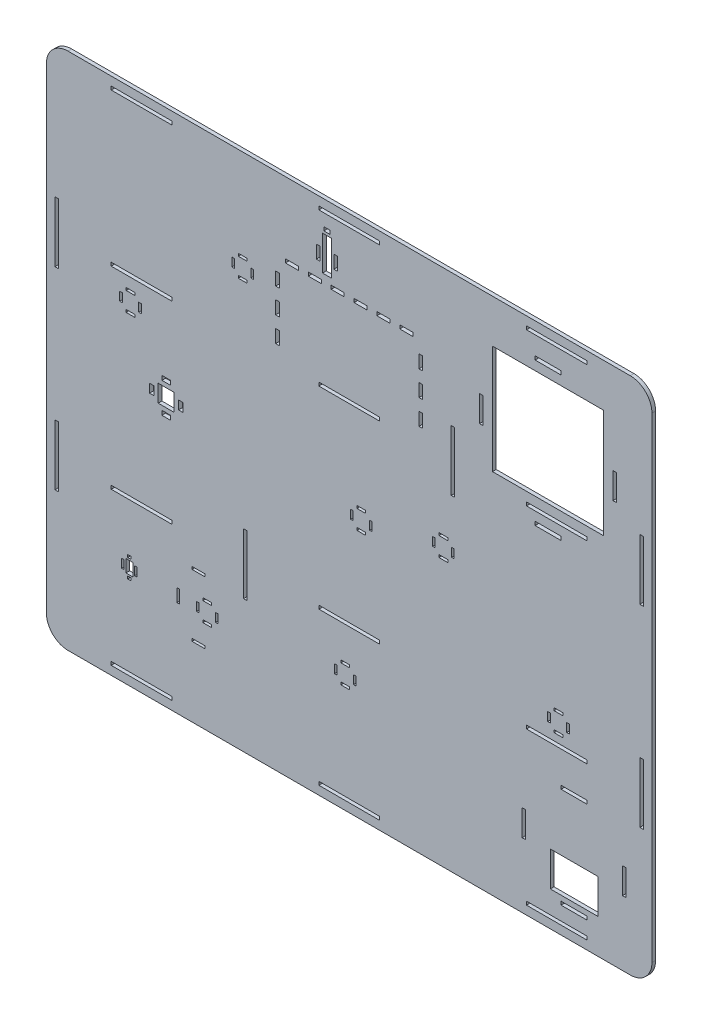
SolidWorks part; units mm, degrees
ref_plane "Front Plane" through (0, 0, 0) normal (0, 0, 1) x (1, 0, 0)
ref_plane "Top Plane" through (0, 0, 0) normal (0, 1, 0) x (1, 0, 0)
ref_plane "Right Plane" through (0, 0, 0) normal (1, 0, 0) x (0, 0, -1)
sketch "Sketch1" plane through (0, 0, 0) normal (0, 0, 1) x (1, 0, 0)
  line L0 (82.85, 113.55) -> (82.85, 215.7) construction
  line L1 (-325, -300) -> (325, -300)
  line L2 (-350, -275) -> (-350, 275)
  line L3 (-325, 300) -> (325, 300)
  line L4 (350, -275) -> (350, 275)
  line L5 (-350, -300) -> (350, 300) construction
  line L6 (-350, 300) -> (350, -300) construction
  line L7 (82.85, 215.7) -> (-82.85, 215.7) construction
  line L8 (-82.85, 215.7) -> (-82.85, 113.55) construction
  line L9 (-35.85, 215.7) -> (-35.85, 270) construction
  line L10 (-35.85, 270) -> (-15.55, 270) construction
  line L11 (-15.55, 270) -> (-15.55, 215.7) construction
  line L12 (-80.75, 142.31) -> (-84.95, 127.21) construction
  line L13 (80.75, 199.87) -> (84.95, 199.87)
  line L14 (80.75, 199.87) -> (80.75, 184.77)
  line L15 (0, 300) -> (0, -300) construction
  line L16 (-350, 0) -> (350, 0) construction
  line L17 (-275, -286) -> (-275, -290)
  line L18 (340, -76.6666) -> (336, -76.6666)
  line L19 (340, -76.6666) -> (340, -146.6666)
  line L20 (340, -146.6666) -> (336, -146.6666)
  line L21 (336, -76.6666) -> (336, -146.6666)
  line L22 (336, 146.6667) -> (340, 146.6667)
  line L23 (336, 146.6667) -> (336, 76.6667)
  line L24 (336, 76.6667) -> (340, 76.6667)
  line L25 (340, 146.6667) -> (340, 76.6667)
  line L30 (-35, -286) -> (35, -286)
  line L31 (-35, -286) -> (-35, -290)
  line L32 (-35, -290) -> (35, -290)
  line L33 (35, -286) -> (35, -290)
  line L34 (205, -286) -> (275, -286)
  line L35 (205, -286) -> (205, -290)
  line L36 (205, -290) -> (275, -290)
  line L37 (275, -286) -> (275, -290)
  line L38 (-205, -290) -> (-275, -290)
  line L39 (-205, -286) -> (-205, -290)
  line L40 (-205, -286) -> (-275, -286)
  line L45 (-340, 146.6667) -> (-340, 76.6667)
  line L46 (-336, 76.6667) -> (-340, 76.6667)
  line L47 (-336, 146.6667) -> (-336, 76.6667)
  line L48 (-336, 146.6667) -> (-340, 146.6667)
  line L49 (-336, -76.6666) -> (-336, -146.6666)
  line L50 (-340, -146.6666) -> (-336, -146.6666)
  line L51 (-340, -76.6666) -> (-340, -146.6666)
  line L52 (-340, -76.6666) -> (-336, -76.6666)
  line L61 (80.75, 184.77) -> (84.95, 184.77)
  line L62 (84.95, 199.87) -> (84.95, 184.77)
  line L63 (80.75, 199.87) -> (84.95, 184.77) construction
  line L64 (-340, 290) -> (340, 290) construction
  line L65 (340, -290) -> (340, 290) construction
  line L66 (-340, -290) -> (340, -290) construction
  line L67 (-340, -290) -> (-340, 290) construction
  line L72 (122, 146.6667) -> (118, 146.6667)
  line L73 (122, 146.6667) -> (122, 76.6667)
  line L74 (122, 76.6667) -> (118, 76.6667)
  line L75 (118, 146.6667) -> (118, 76.6667)
  line L80 (-330, 280) -> (330, 280) construction
  line L81 (330, -280) -> (330, 280) construction
  line L82 (-330, -280) -> (330, -280) construction
  line L83 (-330, -280) -> (-330, 280) construction
  line L84 (-118, -146.6667) -> (-118, -76.6667)
  line L85 (-118, -76.6667) -> (-122, -76.6667)
  line L86 (-122, -146.6667) -> (-122, -76.6667)
  line L87 (-118, -146.6667) -> (-122, -146.6667)
  line L92 (-35, 113.6667) -> (35, 113.6667)
  line L93 (-35, 113.6667) -> (-35, 109.6667)
  line L94 (-35, 109.6667) -> (35, 109.6667)
  line L95 (35, 113.6667) -> (35, 109.6667)
  line L96 (-275, 113.6667) -> (-205, 113.6667)
  line L97 (-275, 113.6667) -> (-275, 109.6667)
  line L98 (-275, 109.6667) -> (-205, 109.6667)
  line L99 (-205, 113.6667) -> (-205, 109.6667)
  line L100 (205, 113.6667) -> (275, 113.6667)
  line L101 (205, 113.6667) -> (205, 109.6667)
  line L102 (205, 109.6667) -> (275, 109.6667)
  line L103 (275, 113.6667) -> (275, 109.6667)
  line L104 (-275, -113.6667) -> (-275, -109.6667)
  line L105 (-275, -109.6667) -> (-205, -109.6667)
  line L106 (-205, -113.6667) -> (-205, -109.6667)
  line L107 (-275, -113.6667) -> (-205, -113.6667)
  line L108 (-35, -113.6667) -> (-35, -109.6667)
  line L109 (-35, -109.6667) -> (35, -109.6667)
  line L110 (35, -113.6667) -> (35, -109.6667)
  line L111 (-35, -113.6667) -> (35, -113.6667)
  line L112 (205, -113.6667) -> (205, -109.6667)
  line L113 (205, -109.6667) -> (275, -109.6667)
  line L114 (275, -113.6667) -> (275, -109.6667)
  line L115 (205, -113.6667) -> (275, -113.6667)
  line L116 (-205, 286) -> (-275, 286)
  line L117 (-205, 286) -> (-205, 290)
  line L118 (-205, 290) -> (-275, 290)
  line L119 (-275, 286) -> (-275, 290)
  line L120 (-35, 290) -> (35, 290)
  line L121 (35, 286) -> (35, 290)
  line L122 (-35, 286) -> (35, 286)
  line L123 (-35, 286) -> (-35, 290)
  line L124 (205, 290) -> (275, 290)
  line L125 (275, 286) -> (275, 290)
  line L126 (205, 286) -> (275, 286)
  line L127 (205, 286) -> (205, 290)
  line L128 (-338, -288) -> (-338, 288) construction
  line L129 (-338, 288) -> (338, 288) construction
  line L130 (338, -288) -> (338, 288) construction
  line L131 (-338, -288) -> (338, -288) construction
  line L132 (80.75, 184.77) -> (84.95, 199.87) construction
  line L133 (80.75, 155.99) -> (84.95, 155.99)
  line L134 (80.75, 155.99) -> (80.75, 171.09)
  line L135 (80.75, 171.09) -> (84.95, 171.09)
  line L136 (84.95, 155.99) -> (84.95, 171.09)
  line L137 (80.75, 155.99) -> (84.95, 171.09) construction
  line L138 (80.75, 171.09) -> (84.95, 155.99) construction
  line L139 (80.75, 127.21) -> (84.95, 127.21)
  line L140 (80.75, 127.21) -> (80.75, 142.31)
  line L141 (80.75, 142.31) -> (84.95, 142.31)
  line L142 (84.95, 127.21) -> (84.95, 142.31)
  line L143 (80.75, 127.21) -> (84.95, 142.31) construction
  line L144 (80.75, 142.31) -> (84.95, 127.21) construction
  line L145 (-80.75, 127.21) -> (-84.95, 142.31) construction
  line L146 (-80.75, 171.09) -> (-84.95, 155.99) construction
  line L147 (-80.75, 155.99) -> (-84.95, 171.09) construction
  line L148 (-80.75, 184.77) -> (-84.95, 199.87) construction
  line L149 (-80.75, 199.87) -> (-84.95, 184.77) construction
  line L150 (-84.95, 127.21) -> (-84.95, 142.31)
  line L151 (-80.75, 142.31) -> (-84.95, 142.31)
  line L152 (-80.75, 127.21) -> (-80.75, 142.31)
  line L153 (-80.75, 127.21) -> (-84.95, 127.21)
  line L154 (-84.95, 155.99) -> (-84.95, 171.09)
  line L155 (-80.75, 171.09) -> (-84.95, 171.09)
  line L156 (-80.75, 155.99) -> (-80.75, 171.09)
  line L157 (-80.75, 155.99) -> (-84.95, 155.99)
  line L158 (-84.95, 199.87) -> (-84.95, 184.77)
  line L159 (-80.75, 184.77) -> (-84.95, 184.77)
  line L160 (-80.75, 199.87) -> (-80.75, 184.77)
  line L161 (-80.75, 199.87) -> (-84.95, 199.87)
  line L162 (320, -270) -> (320, -150) construction
  line L163 (-73.65, 213.6) -> (-58.55, 213.6)
  line L164 (-73.65, 213.6) -> (-73.65, 217.8)
  line L165 (-73.65, 217.8) -> (-58.55, 217.8)
  line L166 (-58.55, 213.6) -> (-58.55, 217.8)
  line L167 (-73.65, 213.6) -> (-58.55, 217.8) construction
  line L168 (-73.65, 217.8) -> (-58.55, 213.6) construction
  line L169 (-47.21, 213.6) -> (-32.11, 213.6)
  line L170 (-47.21, 213.6) -> (-47.21, 217.8)
  line L171 (-47.21, 217.8) -> (-32.11, 217.8)
  line L172 (-32.11, 213.6) -> (-32.11, 217.8)
  line L173 (-47.21, 213.6) -> (-32.11, 217.8) construction
  line L174 (-47.21, 217.8) -> (-32.11, 213.6) construction
  line L175 (-20.77, 213.6) -> (-5.67, 213.6)
  line L176 (-20.77, 213.6) -> (-20.77, 217.8)
  line L177 (-20.77, 217.8) -> (-5.67, 217.8)
  line L178 (-5.67, 213.6) -> (-5.67, 217.8)
  line L179 (-20.77, 213.6) -> (-5.67, 217.8) construction
  line L180 (-20.77, 217.8) -> (-5.67, 213.6) construction
  line L181 (5.67, 213.6) -> (20.77, 213.6)
  line L182 (5.67, 213.6) -> (5.67, 217.8)
  line L183 (5.67, 217.8) -> (20.77, 217.8)
  line L184 (20.77, 213.6) -> (20.77, 217.8)
  line L185 (5.67, 213.6) -> (20.77, 217.8) construction
  line L186 (5.67, 217.8) -> (20.77, 213.6) construction
  line L187 (32.11, 213.6) -> (47.21, 213.6)
  line L188 (32.11, 213.6) -> (32.11, 217.8)
  line L189 (32.11, 217.8) -> (47.21, 217.8)
  line L190 (47.21, 213.6) -> (47.21, 217.8)
  line L191 (32.11, 213.6) -> (47.21, 217.8) construction
  line L192 (32.11, 217.8) -> (47.21, 213.6) construction
  line L193 (58.55, 213.6) -> (73.65, 213.6)
  line L194 (58.55, 213.6) -> (58.55, 217.8)
  line L195 (58.55, 217.8) -> (73.65, 217.8)
  line L196 (73.65, 213.6) -> (73.65, 217.8)
  line L197 (58.55, 213.6) -> (73.65, 217.8) construction
  line L198 (58.55, 217.8) -> (73.65, 213.6) construction
  line L199 (-17.65, 250.4) -> (-13.45, 250.4)
  line L200 (-17.65, 250.4) -> (-17.65, 235.3)
  line L201 (-17.65, 235.3) -> (-13.45, 235.3)
  line L202 (-13.45, 250.4) -> (-13.45, 235.3)
  line L203 (-17.65, 250.4) -> (-13.45, 235.3) construction
  line L204 (-17.65, 235.3) -> (-13.45, 250.4) construction
  line L205 (-37.95, 250.4) -> (-33.75, 250.4)
  line L206 (-37.95, 250.4) -> (-37.95, 235.3)
  line L207 (-37.95, 235.3) -> (-33.75, 235.3)
  line L208 (-33.75, 250.4) -> (-33.75, 235.3)
  line L209 (-37.95, 250.4) -> (-33.75, 235.3) construction
  line L210 (-37.95, 235.3) -> (-33.75, 250.4) construction
  line L211 (-29.25, 267.9) -> (-22.15, 267.9)
  line L212 (-29.25, 267.9) -> (-29.25, 272.1)
  line L213 (-29.25, 272.1) -> (-22.15, 272.1)
  line L214 (-22.15, 267.9) -> (-22.15, 272.1)
  line L215 (-29.25, 267.9) -> (-22.15, 272.1) construction
  line L216 (-29.25, 272.1) -> (-22.15, 267.9) construction
  line L217 (-30.75, 264.9) -> (-20.65, 264.9)
  line L218 (-30.75, 264.9) -> (-30.75, 224.9)
  line L219 (-30.75, 224.9) -> (-20.65, 224.9)
  line L220 (-20.65, 264.9) -> (-20.65, 224.9)
  line L221 (320, -150) -> (200, -150) construction
  line L222 (200, -150) -> (200, -270) construction
  line L223 (200, -270) -> (320, -270) construction
  line L224 (229.5, -101.3683) -> (254.5, -101.3683) construction
  line L225 (275, -270) -> (245, -270)
  line L226 (275, -270) -> (275, -266)
  line L227 (275, -266) -> (245, -266)
  line L228 (245, -270) -> (245, -266)
  line L229 (200, -225) -> (204, -225)
  line L230 (200, -225) -> (200, -195)
  line L231 (200, -195) -> (204, -195)
  line L232 (204, -225) -> (204, -195)
  line L233 (245, -150) -> (275, -150)
  line L234 (245, -150) -> (245, -154)
  line L235 (245, -154) -> (275, -154)
  line L236 (275, -150) -> (275, -154)
  line L237 (320, -195) -> (316, -195)
  line L238 (320, -195) -> (320, -225)
  line L239 (320, -225) -> (316, -225)
  line L240 (316, -195) -> (316, -225)
  line L241 (232.5, -260) -> (287.5, -260)
  line L242 (232.5, -260) -> (232.5, -220)
  line L243 (232.5, -220) -> (287.5, -220)
  line L244 (287.5, -260) -> (287.5, -220)
  line L245 (-263, -193.95) -> (-245, -193.95) construction
  line L246 (-263, -193.95) -> (-263, -169.45) construction
  line L247 (-263, -169.45) -> (-245, -169.45) construction
  line L248 (-245, -193.95) -> (-245, -169.45) construction
  line L249 (-245, -176.7) -> (-248, -176.7)
  line L250 (-245, -176.7) -> (-245, -186.7)
  line L251 (-245, -186.7) -> (-248, -186.7)
  line L252 (-248, -176.7) -> (-248, -186.7)
  line L253 (-256, -193.95) -> (-252, -193.95)
  line L254 (-256, -193.95) -> (-256, -190.95)
  line L255 (-256, -190.95) -> (-252, -190.95)
  line L256 (-252, -193.95) -> (-252, -190.95)
  line L257 (-263, -186.7) -> (-260, -186.7)
  line L258 (-263, -186.7) -> (-263, -176.7)
  line L259 (-263, -176.7) -> (-260, -176.7)
  line L260 (-260, -186.7) -> (-260, -176.7)
  line L261 (-256, -169.45) -> (-252, -169.45)
  line L262 (-256, -169.45) -> (-256, -172.45)
  line L263 (-256, -172.45) -> (-252, -172.45)
  line L264 (-252, -169.45) -> (-252, -172.45)
  line L265 (-230.7, -10.34) -> (-192.2, -10.34) construction
  line L266 (-230.7, -10.34) -> (-230.7, 29.66) construction
  line L267 (-230.7, 29.66) -> (-192.2, 29.66) construction
  line L268 (-192.2, -10.34) -> (-192.2, 29.66) construction
  line L269 (-192.2, 14.66) -> (-197.2, 14.66)
  line L270 (-192.2, 14.66) -> (-192.2, 4.66)
  line L271 (-192.2, 4.66) -> (-197.2, 4.66)
  line L272 (-197.2, 14.66) -> (-197.2, 4.66)
  line L273 (-230.7, 14.66) -> (-225.7, 14.66)
  line L274 (-230.7, 14.66) -> (-230.7, 4.66)
  line L275 (-230.7, 4.66) -> (-225.7, 4.66)
  line L276 (-225.7, 14.66) -> (-225.7, 4.66)
  line L277 (-206.45, -10.34) -> (-216.45, -10.34)
  line L278 (-206.45, -10.34) -> (-206.45, -5.34)
  line L279 (-206.45, -5.34) -> (-216.45, -5.34)
  line L280 (-216.45, -10.34) -> (-216.45, -5.34)
  line L281 (-216.45, 29.66) -> (-206.45, 29.66)
  line L282 (-216.45, 29.66) -> (-216.45, 24.66)
  line L283 (-216.45, 24.66) -> (-206.45, 24.66)
  line L284 (-206.45, 29.66) -> (-206.45, 24.66)
  line L285 (-220.7, -0.34) -> (-202.2, -0.34)
  line L286 (-220.7, -0.34) -> (-220.7, 19.66)
  line L287 (-220.7, 19.66) -> (-202.2, 19.66)
  line L288 (-202.2, -0.34) -> (-202.2, 19.66)
  line L289 (-258, -188.95) -> (-250, -188.95)
  line L290 (-258, -188.95) -> (-258, -174.45)
  line L291 (-258, -174.45) -> (-250, -174.45)
  line L292 (-250, -188.95) -> (-250, -174.45)
  line L293 (-199, -219.2) -> (-149, -219.2) construction
  line L294 (-199, -219.2) -> (-199, -144.2) construction
  line L295 (-199, -144.2) -> (-149, -144.2) construction
  line L296 (-149, -219.2) -> (-149, -144.2) construction
  line L297 (-181.5, -219.2) -> (-166.5, -219.2)
  line L298 (-181.5, -219.2) -> (-181.5, -216.2)
  line L299 (-181.5, -216.2) -> (-166.5, -216.2)
  line L300 (-166.5, -219.2) -> (-166.5, -216.2)
  line L301 (-166.5, -144.2) -> (-181.5, -144.2)
  line L302 (-166.5, -144.2) -> (-166.5, -147.2)
  line L303 (-166.5, -147.2) -> (-181.5, -147.2)
  line L304 (-181.5, -144.2) -> (-181.5, -147.2)
  line L305 (-199, -189.2) -> (-196, -189.2)
  line L306 (-199, -189.2) -> (-199, -174.2)
  line L307 (-199, -174.2) -> (-196, -174.2)
  line L308 (-196, -189.2) -> (-196, -174.2)
  line L313 (-176.5, -194.2) -> (-151.5, -194.2) construction
  line L314 (-176.5, -194.2) -> (-176.5, -169.2) construction
  line L315 (-176.5, -169.2) -> (-151.5, -169.2) construction
  line L316 (-151.5, -194.2) -> (-151.5, -169.2) construction
  line L317 (-176.5, -194.2) -> (-151.5, -169.2) construction
  line L318 (-176.5, -169.2) -> (-151.5, -194.2) construction
  line L319 (-169, -169.2) -> (-159, -169.2)
  line L320 (-169, -169.2) -> (-169, -172.2)
  line L321 (-169, -172.2) -> (-159, -172.2)
  line L322 (-159, -169.2) -> (-159, -172.2)
  line L323 (-151.5, -176.7) -> (-154.5, -176.7)
  line L324 (-151.5, -176.7) -> (-151.5, -186.7)
  line L325 (-151.5, -186.7) -> (-154.5, -186.7)
  line L326 (-154.5, -176.7) -> (-154.5, -186.7)
  line L327 (-159, -194.2) -> (-169, -194.2)
  line L328 (-159, -194.2) -> (-159, -191.2)
  line L329 (-159, -191.2) -> (-169, -191.2)
  line L330 (-169, -194.2) -> (-169, -191.2)
  line L331 (-176.5, -186.7) -> (-173.5, -186.7)
  line L332 (-176.5, -186.7) -> (-176.5, -176.7)
  line L333 (-176.5, -176.7) -> (-173.5, -176.7)
  line L334 (-173.5, -186.7) -> (-173.5, -176.7)
  line L335 (1.65, -12.8333) -> (26.65, -12.8333) construction
  line L336 (1.65, -12.8333) -> (1.65, 12.1667) construction
  line L337 (1.65, 12.1667) -> (26.65, 12.1667) construction
  line L338 (26.65, -12.8333) -> (26.65, 12.1667) construction
  line L339 (1.65, -12.8333) -> (26.65, 12.1667) construction
  line L340 (1.65, 12.1667) -> (26.65, -12.8333) construction
  line L341 (9.15, 12.1667) -> (19.15, 12.1667)
  line L342 (9.15, 12.1667) -> (9.15, 9.1667)
  line L343 (9.15, 9.1667) -> (19.15, 9.1667)
  line L344 (19.15, 12.1667) -> (19.15, 9.1667)
  line L345 (26.65, 4.6667) -> (23.65, 4.6667)
  line L346 (26.65, 4.6667) -> (26.65, -5.3333)
  line L347 (26.65, -5.3333) -> (23.65, -5.3333)
  line L348 (23.65, 4.6667) -> (23.65, -5.3333)
  line L349 (9.15, -12.8333) -> (19.15, -12.8333)
  line L350 (9.15, -12.8333) -> (9.15, -9.8333)
  line L351 (9.15, -9.8333) -> (19.15, -9.8333)
  line L352 (19.15, -12.8333) -> (19.15, -9.8333)
  line L353 (1.65, 4.6667) -> (4.65, 4.6667)
  line L354 (1.65, 4.6667) -> (1.65, -5.3333)
  line L355 (1.65, -5.3333) -> (4.65, -5.3333)
  line L356 (4.65, 4.6667) -> (4.65, -5.3333)
  line L357 (229.5, -101.3683) -> (229.5, -76.3683) construction
  line L358 (229.5, -76.3683) -> (254.5, -76.3683) construction
  line L359 (254.5, -101.3683) -> (254.5, -76.3683) construction
  line L392 (350, -300) -> (350, 300) construction
  line L393 (-17, -176.7) -> (8, -176.7) construction
  line L394 (-17, -176.7) -> (-17, -151.7) construction
  line L395 (-17, -151.7) -> (8, -151.7) construction
  line L396 (8, -176.7) -> (8, -151.7) construction
  line L397 (-17, -159.2) -> (-14, -159.2)
  line L398 (-17, -159.2) -> (-17, -169.2)
  line L399 (-17, -169.2) -> (-14, -169.2)
  line L400 (-14, -159.2) -> (-14, -169.2)
  line L401 (-9.5, -151.7) -> (0.5, -151.7)
  line L402 (-9.5, -151.7) -> (-9.5, -154.7)
  line L403 (-9.5, -154.7) -> (0.5, -154.7)
  line L404 (0.5, -151.7) -> (0.5, -154.7)
  line L405 (8, -159.2) -> (5, -159.2)
  line L406 (8, -159.2) -> (8, -169.2)
  line L407 (8, -169.2) -> (5, -169.2)
  line L408 (5, -159.2) -> (5, -169.2)
  line L409 (0.5, -176.7) -> (-9.5, -176.7)
  line L410 (0.5, -176.7) -> (0.5, -173.7)
  line L411 (0.5, -173.7) -> (-9.5, -173.7)
  line L412 (-9.5, -176.7) -> (-9.5, -173.7)
  line L413 (-350, 300) -> (350, 300) construction
  line L414 (-350, -300) -> (350, -300) construction
  line L415 (-350, -300) -> (-350, 300) construction
  line L416 (-135.549, 171.0614) -> (-110.549, 171.0614) construction
  line L417 (96.5, 7.41) -> (121.5, 7.41) construction
  line L418 (96.5, 7.41) -> (96.5, 32.41) construction
  line L419 (96.5, 32.41) -> (121.5, 32.41) construction
  line L420 (121.5, 7.41) -> (121.5, 32.41) construction
  line L421 (96.5, 7.41) -> (121.5, 32.41) construction
  line L422 (96.5, 32.41) -> (121.5, 7.41) construction
  line L423 (96.5, 24.91) -> (99.5, 24.91)
  line L424 (96.5, 24.91) -> (96.5, 14.91)
  line L425 (96.5, 14.91) -> (99.5, 14.91)
  line L426 (99.5, 24.91) -> (99.5, 14.91)
  line L427 (121.5, 14.91) -> (118.5, 14.91)
  line L428 (121.5, 14.91) -> (121.5, 24.91)
  line L429 (121.5, 24.91) -> (118.5, 24.91)
  line L430 (118.5, 14.91) -> (118.5, 24.91)
  line L431 (114, 32.41) -> (104, 32.41)
  line L432 (114, 32.41) -> (114, 29.41)
  line L433 (114, 29.41) -> (104, 29.41)
  line L434 (104, 32.41) -> (104, 29.41)
  line L435 (104, 7.41) -> (114, 7.41)
  line L436 (104, 7.41) -> (104, 10.41)
  line L437 (104, 10.41) -> (114, 10.41)
  line L438 (114, 7.41) -> (114, 10.41)
  line L439 (229.5, -101.3683) -> (254.5, -76.3683) construction
  line L440 (229.5, -76.3683) -> (254.5, -101.3683) construction
  line L441 (229.5, -83.8683) -> (232.5, -83.8683)
  line L442 (229.5, -83.8683) -> (229.5, -93.8683)
  line L443 (229.5, -93.8683) -> (232.5, -93.8683)
  line L444 (232.5, -83.8683) -> (232.5, -93.8683)
  line L445 (254.5, -93.8683) -> (251.5, -93.8683)
  line L446 (254.5, -93.8683) -> (254.5, -83.8683)
  line L447 (254.5, -83.8683) -> (251.5, -83.8683)
  line L448 (251.5, -93.8683) -> (251.5, -83.8683)
  line L449 (247, -76.3683) -> (237, -76.3683)
  line L450 (247, -76.3683) -> (247, -79.3683)
  line L451 (247, -79.3683) -> (237, -79.3683)
  line L452 (237, -76.3683) -> (237, -79.3683)
  line L453 (237, -101.3683) -> (247, -101.3683)
  line L454 (237, -101.3683) -> (237, -98.3683)
  line L455 (237, -98.3683) -> (247, -98.3683)
  line L456 (247, -101.3683) -> (247, -98.3683)
  line L457 (34.8, 109.3667) -> (47.7, 109.3667) construction
  line L458 (-265.2474, 71.9826) -> (-240.2474, 71.9826) construction
  line L459 (-265.2474, 71.9826) -> (-265.2474, 96.9826) construction
  line L460 (-265.2474, 96.9826) -> (-240.2474, 96.9826) construction
  line L461 (-240.2474, 71.9826) -> (-240.2474, 96.9826) construction
  line L462 (-265.2474, 71.9826) -> (-240.2474, 96.9826) construction
  line L463 (-265.2474, 96.9826) -> (-240.2474, 71.9826) construction
  line L464 (-265.2474, 89.4826) -> (-262.2474, 89.4826)
  line L465 (-265.2474, 89.4826) -> (-265.2474, 79.4826)
  line L466 (-265.2474, 79.4826) -> (-262.2474, 79.4826)
  line L467 (-262.2474, 89.4826) -> (-262.2474, 79.4826)
  line L468 (-240.2474, 79.4826) -> (-243.2474, 79.4826)
  line L469 (-240.2474, 79.4826) -> (-240.2474, 89.4826)
  line L470 (-240.2474, 89.4826) -> (-243.2474, 89.4826)
  line L471 (-243.2474, 79.4826) -> (-243.2474, 89.4826)
  line L472 (-247.7474, 96.9826) -> (-257.7474, 96.9826)
  line L473 (-247.7474, 96.9826) -> (-247.7474, 93.9826)
  line L474 (-247.7474, 93.9826) -> (-257.7474, 93.9826)
  line L475 (-257.7474, 96.9826) -> (-257.7474, 93.9826)
  line L476 (-257.7474, 71.9826) -> (-247.7474, 71.9826)
  line L477 (-257.7474, 71.9826) -> (-257.7474, 74.9826)
  line L478 (-257.7474, 74.9826) -> (-247.7474, 74.9826)
  line L479 (-247.7474, 71.9826) -> (-247.7474, 74.9826)
  line L480 (-135.549, 171.0614) -> (-135.549, 196.0614) construction
  line L481 (-135.549, 196.0614) -> (-110.549, 196.0614) construction
  line L482 (-110.549, 171.0614) -> (-110.549, 196.0614) construction
  line L483 (-135.549, 171.0614) -> (-110.549, 196.0614) construction
  line L484 (-135.549, 196.0614) -> (-110.549, 171.0614) construction
  line L485 (-135.549, 188.5614) -> (-132.549, 188.5614)
  line L486 (-135.549, 188.5614) -> (-135.549, 178.5614)
  line L487 (-135.549, 178.5614) -> (-132.549, 178.5614)
  line L488 (-132.549, 188.5614) -> (-132.549, 178.5614)
  line L489 (-110.549, 178.5614) -> (-113.549, 178.5614)
  line L490 (-110.549, 178.5614) -> (-110.549, 188.5614)
  line L491 (-110.549, 188.5614) -> (-113.549, 188.5614)
  line L492 (-113.549, 178.5614) -> (-113.549, 188.5614)
  line L493 (-118.049, 196.0614) -> (-128.049, 196.0614)
  line L494 (-118.049, 196.0614) -> (-118.049, 193.0614)
  line L495 (-118.049, 193.0614) -> (-128.049, 193.0614)
  line L496 (-128.049, 196.0614) -> (-128.049, 193.0614)
  line L497 (-128.049, 171.0614) -> (-118.049, 171.0614)
  line L498 (-128.049, 171.0614) -> (-128.049, 174.0614)
  line L499 (-128.049, 174.0614) -> (-118.049, 174.0614)
  line L500 (-118.049, 171.0614) -> (-118.049, 174.0614)
  line L501 (204.6, 109.3667) -> (34.8, 109.3667) construction
  line L502 (309.3, 95) -> (150.7, 95) construction
  line L503 (309.3, 95) -> (309.3, 265) construction
  line L504 (309.3, 265) -> (150.7, 265) construction
  line L505 (150.7, 95) -> (150.7, 265) construction
  line L506 (309.3, 95) -> (150.7, 265) construction
  line L507 (309.3, 265) -> (150.7, 95) construction
  line L508 (309.3, 195.05) -> (305, 195.05)
  line L509 (309.3, 195.05) -> (309.3, 164.95)
  line L510 (309.3, 164.95) -> (305, 164.95)
  line L511 (305, 195.05) -> (305, 164.95)
  line L512 (214.95, 95) -> (245.05, 95)
  line L513 (214.95, 95) -> (214.95, 99.3)
  line L514 (214.95, 99.3) -> (245.05, 99.3)
  line L515 (245.05, 95) -> (245.05, 99.3)
  line L516 (150.7, 164.95) -> (155, 164.95)
  line L517 (150.7, 164.95) -> (150.7, 195.05)
  line L518 (150.7, 195.05) -> (155, 195.05)
  line L519 (155, 164.95) -> (155, 195.05)
  line L520 (214.95, 265) -> (245.05, 265)
  line L521 (214.95, 265) -> (214.95, 260.7)
  line L522 (214.95, 260.7) -> (245.05, 260.7)
  line L523 (245.05, 265) -> (245.05, 260.7)
  line L524 (294.3, 124.3667) -> (165.7, 124.3667)
  line L525 (294.3, 124.3667) -> (294.3, 250)
  line L526 (294.3, 250) -> (165.7, 250)
  line L527 (165.7, 124.3667) -> (165.7, 250)
  arc A0 (350, 275) -> (325, 300) centre (325, 275) ccw
  arc A1 (325, -300) -> (350, -275) centre (325, -275) ccw
  arc A2 (-325, -300) -> (-350, -275) centre (-325, -275) cw
  arc A3 (-350, 275) -> (-325, 300) centre (-325, 275) cw
  point P0 (0, 0)
  point P11 (82.85, 192.32)
  point P16 (0, 215.7)
  point P22 (82.85, 163.54)
  point P53 (35, -288)
  point P57 (0, -286)
  point P73 (82.85, 134.76)
  point P75 (338, -76.6666)
  point P77 (-275, 111.6667)
  point P78 (-336, 111.6667)
  point P85 (120, 146.6667)
  point P86 (340, 111.6667)
  point P91 (340, -111.6666)
  point P92 (-39.66, 215.7)
  point P98 (-205, -111.6667)
  point P100 (35, 111.6667)
  point P101 (118, 111.6667)
  point P102 (240, -290)
  point P103 (-122, -111.6667)
  point P109 (240, 113.6667)
  point P115 (0, 113.6667)
  point P116 (-120, -146.6667)
  point P136 (-82.85, 134.76)
  point P137 (-82.85, 163.54)
  point P144 (-82.85, 192.32)
  point P151 (-66.1, 215.7)
  point P157 (240, 109.6667)
  point P161 (-13.22, 215.7)
  point P166 (13.22, 215.7)
  point P171 (39.66, 215.7)
  point P176 (66.1, 215.7)
  point P183 (-35.85, 242.85)
  point P184 (-15.55, 242.85)
  point P193 (-25.7, 270)
  point P219 (260, -266)
  point P220 (260, -270)
  point P221 (260, -154)
  point P222 (320, -210)
  point P223 (316, -210)
  point P224 (204, -210)
  point P229 (260, -260)
  point P250 (-245, -181.7)
  point P251 (-248, -181.7)
  point P252 (-260, -181.7)
  point P253 (-254, -193.95)
  point P254 (-254, -190.95)
  point P255 (-254, -172.45)
  point P276 (-197.2, 9.66)
  point P277 (-192.2, 9.66)
  point P278 (-225.7, 9.66)
  point P279 (-211.45, 29.66)
  point P280 (-211.45, 24.66)
  point P281 (-211.45, -5.34)
  point P282 (-211.45, -10.34)
  point P283 (-254, -169.45)
  point P288 (-211.45, -0.34)
  point P289 (-202.2, 9.66)
  point P294 (-258, -181.7)
  point P295 (-254, -174.45)
  point P296 (-263, -181.7)
  point P301 (-199, -181.7)
  point P314 (-164, -181.7)
  point P319 (-196, -181.7)
  point P320 (-174, -216.2)
  point P321 (-174, -219.2)
  point P322 (-174, -147.2)
  point P323 (-176.5, -181.7)
  point P340 (-164, -191.2)
  point P341 (-164, -172.2)
  point P342 (-164, -169.2)
  point P343 (-154.5, -181.7)
  point P344 (-173.5, -181.7)
  point P345 (14.15, -0.3333)
  point P366 (4.65, -0.3333)
  point P367 (23.65, -0.3333)
  point P368 (14.15, -9.8333)
  point P369 (14.15, 9.1667)
  point P390 (-14, -164.2)
  point P391 (5, -164.2)
  point P392 (8, -164.2)
  point P393 (-4.5, -173.7)
  point P394 (-4.5, -154.7)
  point P395 (-4.5, -151.7)
  point P409 (109, 19.91)
  point P429 (109, 10.41)
  point P430 (109, 7.41)
  point P431 (109, 29.41)
  point P432 (118.5, 19.91)
  point P433 (99.5, 19.91)
  point P434 (121.5, 19.91)
  point P439 (242, -88.8683)
  point P459 (242, -98.3683)
  point P460 (242, -101.3683)
  point P461 (242, -79.3683)
  point P462 (251.5, -88.8683)
  point P463 (232.5, -88.8683)
  point P464 (254.5, -88.8683)
  point P467 (-252.7474, 84.4826)
  point P487 (-252.7474, 74.9826)
  point P488 (-252.7474, 71.9826)
  point P489 (-252.7474, 93.9826)
  point P490 (-243.2474, 84.4826)
  point P491 (-262.2474, 84.4826)
  point P492 (-240.2474, 84.4826)
  point P494 (-123.049, 183.5614)
  point P514 (-123.049, 174.0614)
  point P515 (-123.049, 171.0614)
  point P516 (-123.049, 193.0614)
  point P517 (-113.549, 183.5614)
  point P518 (-132.549, 183.5614)
  point P519 (-110.549, 183.5614)
  point P522 (230, 180)
  point P539 (305, 180)
  point P540 (155, 180)
  point P541 (230, 99.3)
  point P542 (230, 260.7)
  dimension "D118" = 25
  dimension "D1" = 600
  dimension "D2" = 700
  dimension "D6" = 102.15
  dimension "D7" = 165.7
  dimension "D8" = 47
  dimension "D9" = 54.3
  dimension "D10" = 20.3
  dimension "D11" = 10
  dimension "D12" = 70
  dimension "D13" = 576
  dimension "D14" = 12
  dimension "D15" = 153.3333
  dimension "D16" = 70
  dimension "D17" = 4
  dimension "D18" = 153.3333
  dimension "D19" = 2
  dimension "D20" = 676
  dimension "D21" = 176.3333
  dimension "D22" = 223.3333
  dimension "D23" = 12
  dimension "D24" = 70
  dimension "D25" = 4
  dimension "D26" = 70
  dimension "D27" = 98
  dimension "D28" = 153.3334
  dimension "D29" = 176.3334
  dimension "D30" = 120
  dimension "D31" = 230
  dimension "D32" = 23.38
  dimension "D33" = 15.1
  dimension "D34" = 4.2
  dimension "D35" = 28.78
  dimension "D36" = 28.78
  dimension "D37" = 16.75
  dimension "D39" = 580
  dimension "D40" = 680
  dimension "D41" = 15.1
  dimension "D42" = 4.2
  dimension "D43" = 70
  dimension "D44" = 4
  dimension "D45" = 70
  dimension "D46" = 4
  dimension "D47" = 20
  dimension "D48" = 660
  dimension "D49" = 560
  dimension "D50" = 26.44
  dimension "D51" = 26.44
  dimension "D52" = 26.44
  dimension "D53" = 26.44
  dimension "D54" = 70
  dimension "D55" = 4
  dimension "D56" = 70
  dimension "D57" = 4
  dimension "D58" = 26.44
  dimension "D59" = 100
  dimension "D60" = 27.15
  dimension "D61" = 15.1
  dimension "D62" = 4.2
  dimension "D63" = 7.1
  dimension "D64" = 4.2
  dimension "D65" = 3
  dimension "D66" = 3
  dimension "D67" = 3
  dimension "D68" = 40
  dimension "D69" = 120
  dimension "D70" = 120
  dimension "D71" = 10
  dimension "D72" = 10
  dimension "D73" = 30
  dimension "D74" = 4
  dimension "D75" = 55
  dimension "D76" = 40
  dimension "D77" = 10
  dimension "D78" = 18
  dimension "D79" = 24.5
  dimension "D80" = 4
  dimension "D81" = 3
  dimension "D82" = 10
  dimension "D83" = 3
  dimension "D84" = 67
  dimension "D85" = 118.3
  dimension "D86" = 38.5
  dimension "D87" = 40
  dimension "D88" = 10
  dimension "D89" = 5
  dimension "D90" = 191.36
  dimension "D91" = 42.55
  dimension "D92" = 5
  dimension "D93" = 5
  dimension "D94" = 5
  dimension "D95" = 5
  dimension "D96" = 50
  dimension "D97" = 75
  dimension "D98" = 46
  dimension "D99" = 15
  dimension "D100" = 3
  dimension "D101" = 25
  dimension "D102" = 25
  dimension "D103" = 35
  dimension "D104" = 10
  dimension "D105" = 3
  dimension "D106" = 25
  dimension "D107" = 25
  dimension "D108" = 10
  dimension "D109" = 3
  dimension "D110" = 110
  dimension "D111" = 97
  dimension "D112" = 25
  dimension "D113" = 25
  dimension "D114" = 10
  dimension "D115" = 3
  dimension "D116" = 8
  dimension "D117" = 103.3
  dimension "D119" = 25
  dimension "D120" = 25
  dimension "D121" = 10
  dimension "D122" = 3
  dimension "D123" = 89.4567
  dimension "D124" = 221
  dimension "D125" = 25
  dimension "D126" = 25
  dimension "D127" = 10
  dimension "D128" = 3
  dimension "D129" = 61.1317
  dimension "D130" = 88
  dimension "D131" = 25
  dimension "D132" = 25
  dimension "D133" = 10
  dimension "D134" = 3
  dimension "D135" = 77.2526
  dimension "D136" = 195.5174
  dimension "D137" = 25
  dimension "D138" = 25
  dimension "D139" = 10
  dimension "D140" = 3
  dimension "D141" = 96.4386
  dimension "D142" = 206.951
  dimension "D143" = 170
  dimension "D144" = 158.6
  dimension "D145" = 100
  dimension "D146" = 100
  dimension "D147" = 30.1
  dimension "D148" = 4.3
  dimension "D149" = 15
  dimension "D150" = 15
  dimension "D151" = 15
  dimension "D152" = 15
  dimension "D38" = 10
extrude "Boss-Extrude1" add sketch "Sketch1" along normal blind 4.3
